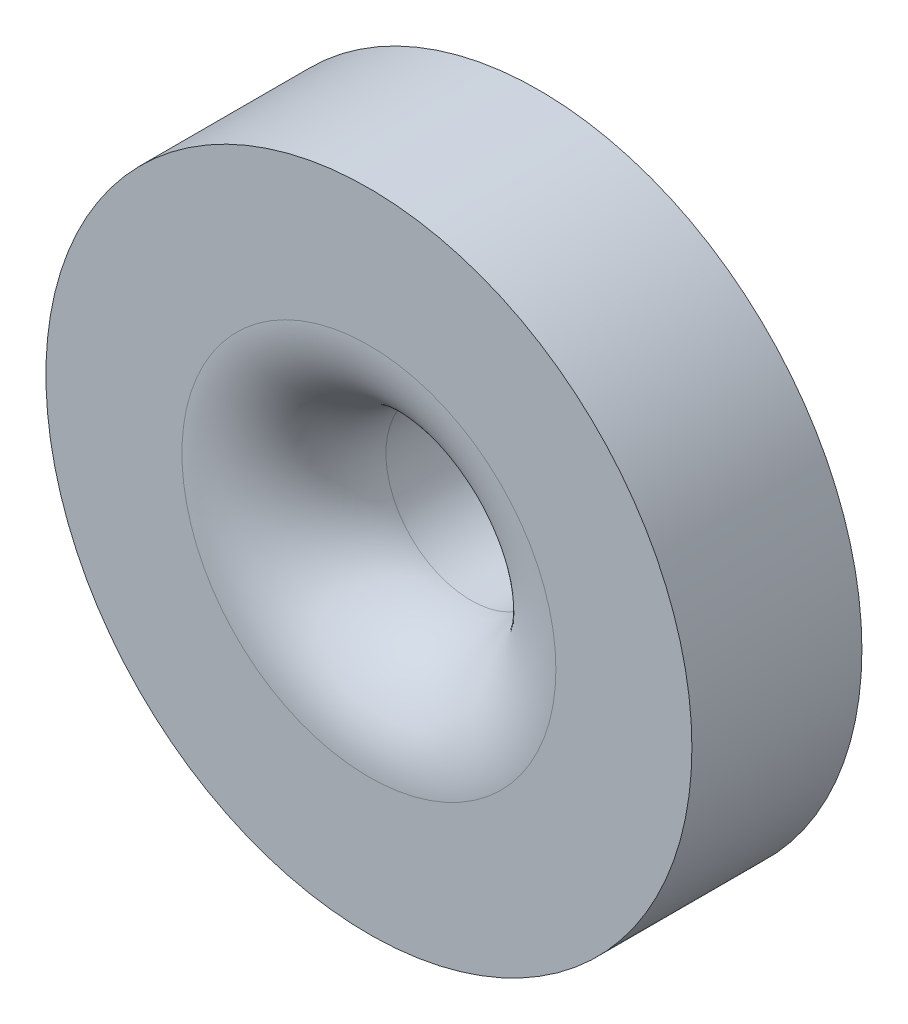
SolidWorks part; units mm, degrees
ref_plane "Front" through (0, 0, 0) normal (0, 0, 1) x (1, 0, 0)
ref_plane "Top" through (0, 0, 0) normal (0, 1, 0) x (1, 0, 0)
ref_plane "Right" through (0, 0, 0) normal (1, 0, 0) x (0, 0, -1)
sketch "Sketch1" plane through (0, 0, 0) normal (0, 0, 1) x (1, 0, 0)
  circle A0 centre (0, 0) radius 9.5
  dimension "D1" = 19
extrude "Boss-Extrude1" add sketch "Sketch1" along normal blind 5
sketch "Sketch2" plane through (0, 0, 5) normal (0, 0, 1) x (1, 0, 0)
  circle A0 centre (0, 0) radius 2.5
  dimension "D1" = 5
extrude "Cut-Extrude1" cut sketch "Sketch2" against normal up to surface (5 mm away) up to face at (9.5, 0, 0)
fillet "Fillet1" radius 3 1 edges at (2.5, 0, 5)
